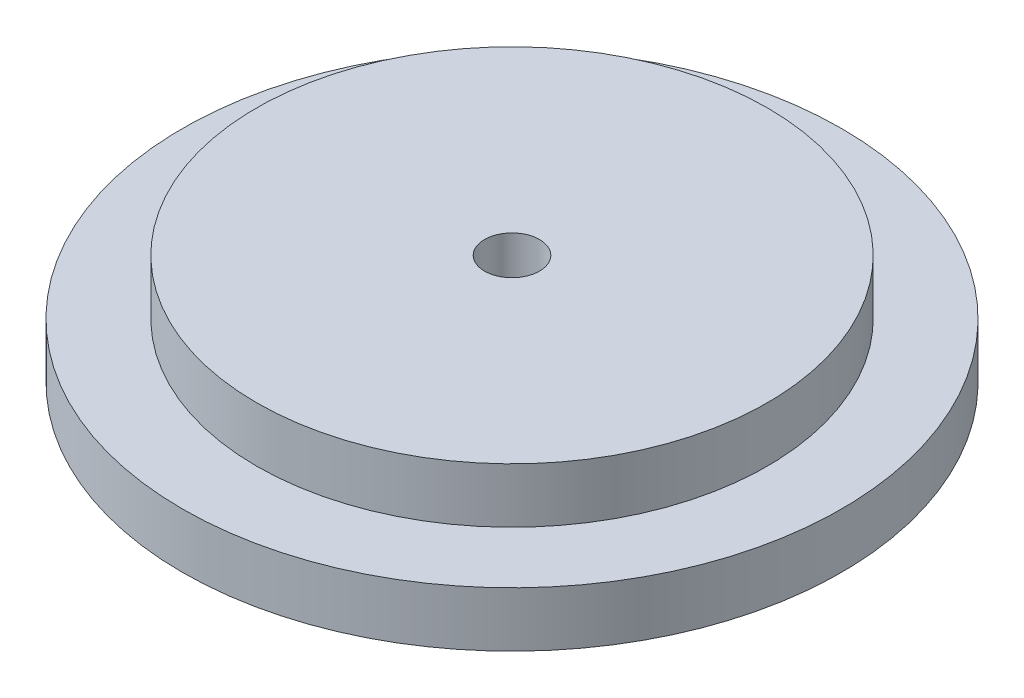
SolidWorks part; units mm, degrees
ref_plane "Plan de face" through (0, 0, 0) normal (0, 0, 1) x (1, 0, 0)
ref_plane "Plan de dessus" through (0, 0, 0) normal (0, 1, 0) x (1, 0, 0)
ref_plane "Plan de droite" through (0, 0, 0) normal (1, 0, 0) x (0, 0, -1)
sketch "Esquisse1" plane through (0, 0, 0) normal (0, 1, 0) x (1, 0, 0)
  circle A0 centre (0, 0) radius 47.9
  dimension "D1" = 95.8
extrude "Boss.-Extru.1" add sketch "Esquisse1" along normal blind 10
sketch "Esquisse2" plane through (0, 0, 0) normal (0, -1, 0) x (1, 0, 0)
  circle A0 centre (0, 0) radius 60
extrude "Boss.-Extru.2" add sketch "Esquisse2" along normal blind 10
sketch "Esquisse4" plane through (0, 10, 0) normal (0, 1, 0) x (1, 0, 0)
  circle A0 centre (0, 0) radius 46.5
  circle M1 centre (0, 0) radius 47.9
extrude "Enlèv. mat.-Extru.1" cut sketch "Esquisse4" against normal up to surface (10 mm away) contours A0 M1 up to face at (0, 0, -47.9)
sketch "Esquisse5" plane through (0, 10, 0) normal (0, 1, 0) x (1, 0, 0)
  circle A0 centre (0, 0) radius 5
  dimension "D1" = 10
extrude "Enlèv. mat.-Extru.2" cut sketch "Esquisse5" against normal through all
